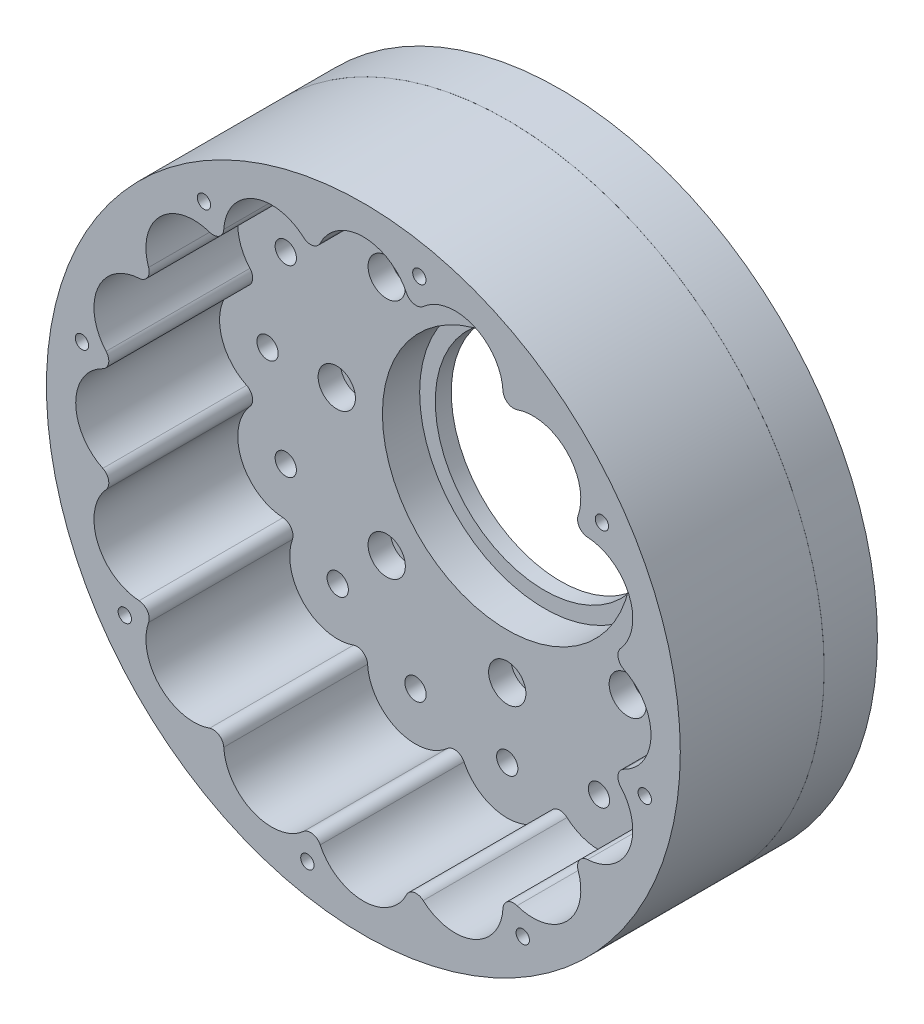
SolidWorks part; units mm, degrees
ref_plane "Front Plane" through (0, 0, 0) normal (0, 0, 1) x (1, 0, 0)
ref_plane "Top Plane" through (0, 0, 0) normal (0, 1, 0) x (1, 0, 0)
ref_plane "Right Plane" through (0, 0, 0) normal (1, 0, 0) x (0, 0, -1)
sketch "Sketch1" plane through (0, 0, 0) normal (0, 0, 1) x (1, 0, 0)
  circle A0 centre (0, 0) radius 59.5
  dimension "D1" = 119
extrude "Boss-Extrude1" add sketch "Sketch1" along normal blind 10
sketch "Sketch2" plane through (0, 0, 10) normal (0, 0, 1) x (1, 0, 0)
  line L0 (0, 0) -> (75.392, 0) construction
  circle A0 centre (0, 0) radius 45 construction
  arc A1 (45.2311, -8.997) -> (45.2311, 8.997) centre (45, 0) ccw
  arc A2 (38.3451, -25.6214) -> (45.2311, -8.997) centre (41.5746, -17.2208) ccw
  arc A3 (25.6214, -38.3451) -> (38.3451, -25.6214) centre (31.8198, -31.8198) ccw
  arc A4 (8.997, -45.2311) -> (25.6214, -38.3451) centre (17.2208, -41.5746) ccw
  arc A5 (-8.997, -45.2311) -> (8.997, -45.2311) centre (0, -45) ccw
  arc A6 (-25.6214, -38.3451) -> (-8.997, -45.2311) centre (-17.2208, -41.5746) ccw
  arc A7 (-38.3451, -25.6214) -> (-25.6214, -38.3451) centre (-31.8198, -31.8198) ccw
  arc A8 (-45.2311, -8.997) -> (-38.3451, -25.6214) centre (-41.5746, -17.2208) ccw
  arc A9 (-45.2311, 8.997) -> (-45.2311, -8.997) centre (-45, 0) ccw
  arc A10 (-38.3451, 25.6214) -> (-45.2311, 8.997) centre (-41.5746, 17.2208) ccw
  arc A11 (-25.6214, 38.3451) -> (-38.3451, 25.6214) centre (-31.8198, 31.8198) ccw
  arc A12 (-8.997, 45.2311) -> (-25.6214, 38.3451) centre (-17.2208, 41.5746) ccw
  arc A13 (8.997, 45.2311) -> (-8.997, 45.2311) centre (0, 45) ccw
  arc A14 (25.6214, 38.3451) -> (8.997, 45.2311) centre (17.2208, 41.5746) ccw
  arc A15 (38.3451, 25.6214) -> (25.6214, 38.3451) centre (31.8198, 31.8198) ccw
  arc A16 (45.2311, 8.997) -> (38.3451, 25.6214) centre (41.5746, 17.2208) ccw
  circle A17 centre (0, 0) radius 59.5
  point P38 (0, 0)
  dimension "D1" = 90
  dimension "D2" = 18
  dimension "D3" = 16
extrude "Boss-Extrude3" add sketch "Sketch2" along normal blind 27
sketch "Sketch3" plane through (0, 0, 10) normal (0, 0, 1) x (1, 0, 0)
  line L0 (0, 0) -> (77.0612, 0) construction
  circle A0 centre (0, 0) radius 45 construction
  circle A1 centre (45, 0) radius 2
  circle A2 centre (41.5746, -17.2208) radius 2
  circle A3 centre (31.8198, -31.8198) radius 2
  circle A4 centre (17.2208, -41.5746) radius 2
  circle A5 centre (0, -45) radius 2
  circle A6 centre (-17.2208, -41.5746) radius 2
  circle A7 centre (-31.8198, -31.8198) radius 2
  circle A8 centre (-41.5746, -17.2208) radius 2
  circle A9 centre (-45, 0) radius 2
  circle A10 centre (-41.5746, 17.2208) radius 2
  circle A11 centre (-31.8198, 31.8198) radius 2
  circle A12 centre (-17.2208, 41.5746) radius 2
  circle A13 centre (0, 45) radius 2
  circle A14 centre (17.2208, 41.5746) radius 2
  circle A15 centre (31.8198, 31.8198) radius 2
  circle A16 centre (41.5746, 17.2208) radius 2
  point P39 (0, 0)
  dimension "D1" = 90
  dimension "D2" = 4
  dimension "D3" = 16
extrude "Cut-Extrude1" cut sketch "Sketch3" against normal blind 4
sketch "Sketch4" plane through (0, 0, 10) normal (0, 0, 1) x (1, 0, 0)
  circle A0 centre (0, 0) radius 23.435
  dimension "D1" = 46.87
extrude "Cut-Extrude2" cut sketch "Sketch4" against normal blind 7
sketch "Sketch5" plane through (0, 0, 3) normal (0, 0, 1) x (1, 0, 0)
  circle A0 centre (0, 0) radius 20.5
  dimension "D1" = 41
extrude "Cut-Extrude3" cut sketch "Sketch5" against normal through all
sketch "Sketch6" plane through (0, 0, 37) normal (0, 0, 1) x (1, 0, 0)
  line L0 (0, 0) -> (73.8619, 0) construction
  line L1 (0, 0) -> (57.2955, 38.2836) construction
  circle A0 centre (44.783, 29.923) radius 1.25
  circle A1 centre (0, 0) radius 53.86 construction
  circle A2 centre (52.8251, -10.5076) radius 1.25
  circle A3 centre (29.923, -44.783) radius 1.25
  circle A4 centre (-10.5076, -52.8251) radius 1.25
  circle A5 centre (-44.783, -29.923) radius 1.25
  circle A6 centre (-52.8251, 10.5076) radius 1.25
  circle A7 centre (-29.923, 44.783) radius 1.25
  circle A8 centre (10.5076, 52.8251) radius 1.25
  point P25 (0, 0)
  dimension "D1" = 107.72
  dimension "D2" = 2.5
  dimension "D3" = 8
extrude "Cut-Extrude4" cut sketch "Sketch6" against normal blind 22
fillet "Fillet1" radius 2 16 edges at (-25.6214, -38.3451, 23.5) (-38.3451, -25.6214, 23.5) (-45.2311, -8.997, 23.5) (-45.2311, 8.997, 23.5) (-8.997, -45.2311, 23.5) (8.997, -45.2311, 23.5) (25.6214, -38.3451, 23.5) (38.3451, -25.6214, 23.5) (45.2311, -8.997, 23.5) (45.2311, 8.997, 23.5) (38.3451, 25.6214, 23.5) (25.6214, 38.3451, 23.5) (8.997, 45.2311, 23.5) (-8.997, 45.2311, 23.5) (-25.6214, 38.3451, 23.5) (-38.3451, 25.6214, 23.5)
sketch "Sketch7" plane through (0, 0, 10) normal (0, 0, 1) x (1, 0, 0)
  line L1 (64.8205, -63.9859) -> (-73.8619, -63.9859)
  line L2 (64.8205, -63.9859) -> (64.8205, 62.1776)
  line L3 (64.8205, 62.1776) -> (-73.8619, 62.1776)
  line L4 (-73.8619, -63.9859) -> (-73.8619, 62.1776)
extrude "Cut-Extrude5" cut sketch "Sketch7" against normal blind 0.01
sketch "Sketch8" plane through (0, 0, 9.99) normal (0, 0, 1) x (1, 0, 0)
  line L0 (0, 0) -> (74.6965, 0) construction
  circle A0 centre (0, 0) radius 32 construction
  circle A2 centre (32, 0) radius 3.5
  circle A3 centre (22.6274, -22.6274) radius 3.5
  circle A4 centre (0, -32) radius 3.5
  circle A5 centre (-22.6274, -22.6274) radius 3.5
  circle A6 centre (-32, 0) radius 3.5
  circle A7 centre (-22.6274, 22.6274) radius 3.5
  circle A8 centre (0, 32) radius 3.5
  circle A9 centre (22.6274, 22.6274) radius 3.5
  point P23 (0, 0)
  dimension "D1" = 64
  dimension "D2" = 7
  dimension "D3" = 8
extrude "Cut-Extrude6" cut sketch "Sketch8" against normal blind 4.2
sketch "Sketch9" plane through (0, 0, 9.99) normal (0, 0, 1) x (1, 0, 0)
  circle A0 centre (0, 0) radius 32 construction
  circle A1 centre (32, 0) radius 2
  circle A2 centre (22.6274, -22.6274) radius 2
  circle A3 centre (0, -32) radius 2
  circle A4 centre (-22.6274, -22.6274) radius 2
  circle A5 centre (-32, 0) radius 2
  circle A6 centre (-22.6274, 22.6274) radius 2
  circle A7 centre (0, 32) radius 2
  circle A8 centre (22.6274, 22.6274) radius 2
  point P22 (0, 0)
  dimension "D1" = 4
  dimension "D2" = 8
extrude "Cut-Extrude7" cut sketch "Sketch9" against normal through all
